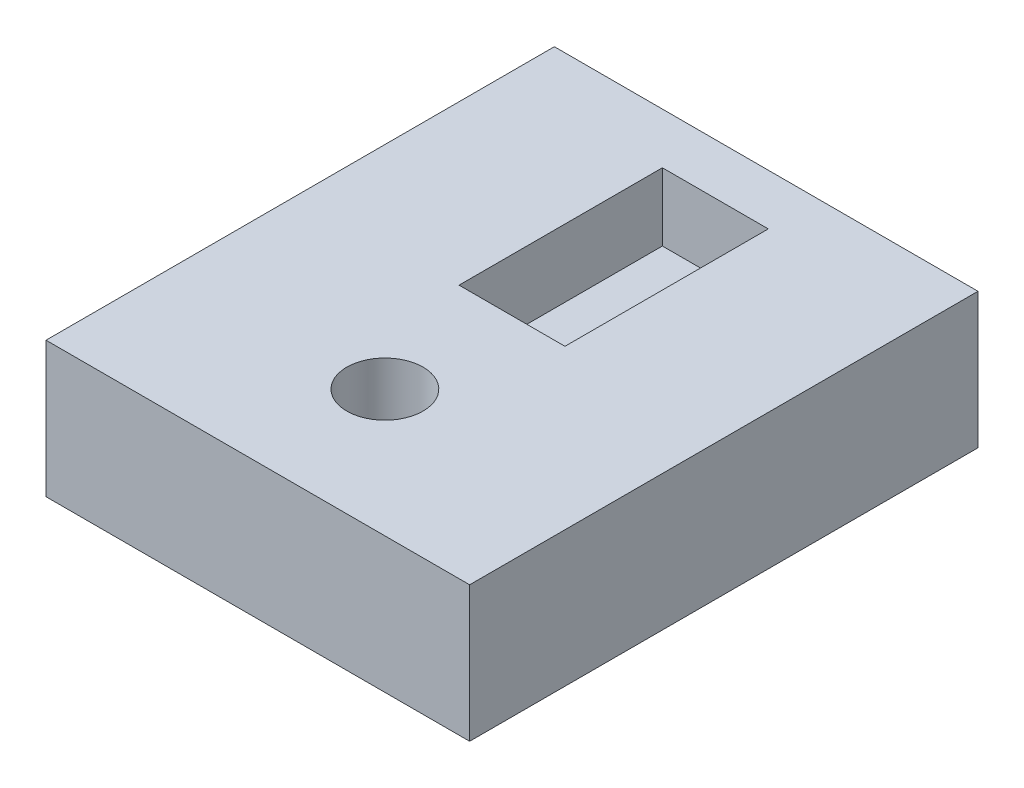
SolidWorks part; units mm, degrees
ref_plane "Front Plane" through (0, 0, 0) normal (0, 0, 1) x (1, 0, 0)
ref_plane "Top Plane" through (0, 0, 0) normal (0, 1, 0) x (1, 0, 0)
ref_plane "Right Plane" through (0, 0, 0) normal (1, 0, 0) x (0, 0, -1)
sketch "Sketch1" plane through (0, 0, 0) normal (0, 0, 1) x (1, 0, 0)
  line L0 (0, 4) -> (0, -4) construction
  line L5 (-12.5, 4) -> (12.5, 4)
  line L14 (-12.5, 4) -> (-12.5, -4)
  line L15 (-12.5, -4) -> (12.5, -4)
  line L16 (12.5, 4) -> (12.5, -4)
  dimension "D1" = 8
  dimension "D2" = 25
extrude "Boss-Extrude1" add sketch "Sketch1" along normal mid plane 30
ref_plane "Plane1" through (0, 0, -12) normal (0, 0, -1) x (-1, 0, 0)
sketch "Sketch3" plane through (0, 0, -12) normal (0, 0, -1) x (-1, 0, 0)
  line L0 (-12.5, 4) -> (12.5, 4) construction
  line L1 (-3.125, 0) -> (3.125, 0)
  line L2 (-3.125, 0) -> (-3.125, 4)
  line L3 (-3.125, 4) -> (3.125, 4)
  line L4 (3.125, 0) -> (3.125, 4)
  line L6 (0, 0) -> (0, 4) construction
  dimension "D1" = 6.25
  dimension "D2" = 4
extrude "Cut-Extrude1" cut sketch "Sketch3" against normal blind 12
hole_wizard "M4 Clearance Hole1" positions "Sketch4" profile "Sketch5" hole size "M4" standard "ANSI Metric" end condition up to next
sketch "Sketch4" plane through (0, -4, 0) normal (0, -1, 0) x (-1, 0, 0)
  line L0 (0, 0) -> (0, -15) construction
  line L1 (-3.125, 0) -> (3.125, 0) construction
  line L2 (12.5, -15) -> (-12.5, -15) construction
  point P0 (0, -7.5)
sketch "Sketch5" plane through (0, -4, 7.5) normal (1, 0, 0) x (0, 0, -1)
  line L0 (0, 0) -> (0, 8)
  line L1 (0, 8) -> (2.25, 8)
  line L2 (2.25, 8) -> (2.25, 0)
  line L5 (2.25, 0) -> (0, 0)
  line L11 (0, -6.35) -> (0, 107.95) construction
  dimension "Thru Hole Dia." = 4.5
  dimension "Thru Hole Depth" = 8
